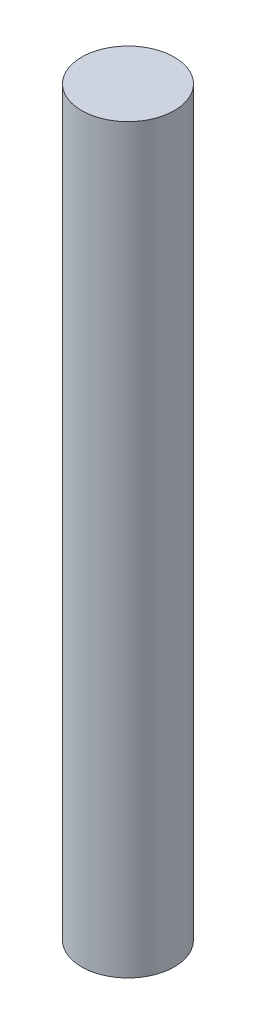
SolidWorks part; units mm, degrees
ref_plane "前视基准面" through (0, 0, 0) normal (0, 0, 1) x (1, 0, 0)
ref_plane "上视基准面" through (0, 0, 0) normal (0, 1, 0) x (1, 0, 0)
ref_plane "右视基准面" through (0, 0, 0) normal (1, 0, 0) x (0, 0, -1)
other "Configuration Table"
sketch "草图1" plane through (0, 0, 0) normal (0, 1, 0) x (1, 0, 0)
  circle A0 centre (0, 0) radius 2.5
  dimension "D1" = 5
extrude "凸台-拉伸1" add sketch "草图1" along normal mid plane 40
